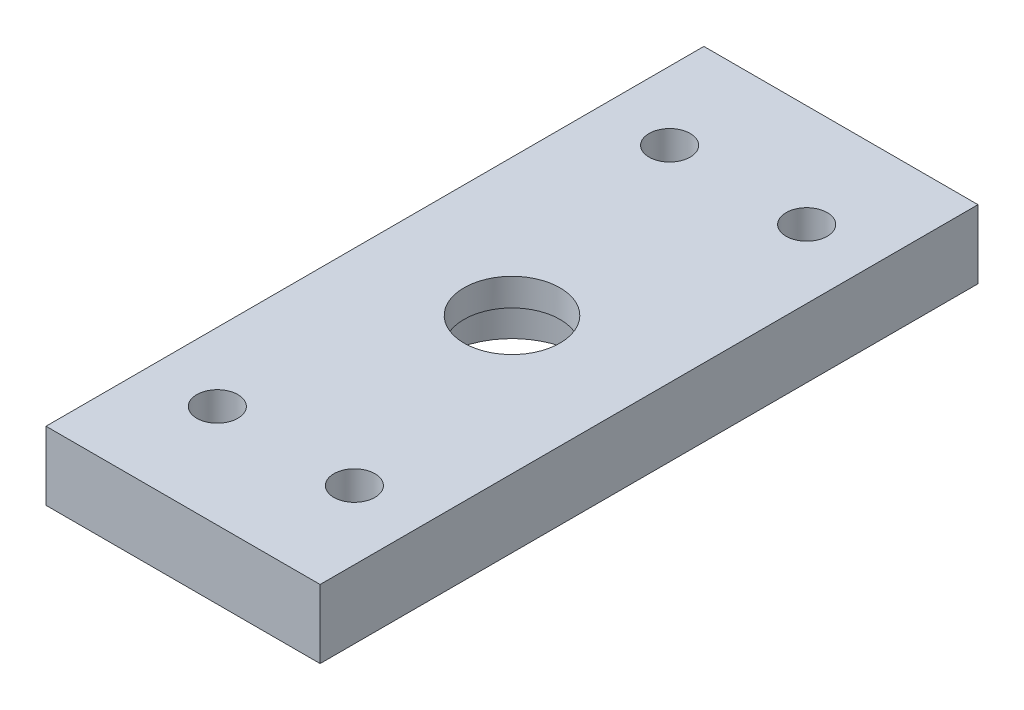
SolidWorks part; units mm, degrees
material "ABS"
ref_plane "Front Plane" through (0, 0, 0) normal (0, 0, 1) x (1, 0, 0)
ref_plane "Top Plane" through (0, 0, 0) normal (0, 1, 0) x (1, 0, 0)
ref_plane "Right Plane" through (0, 0, 0) normal (1, 0, 0) x (0, 0, -1)
sketch "Sketch1" plane through (0, 0, 0) normal (0, 1, 0) x (1, 0, 0)
  line L1 (-10, 24) -> (10, 24)
  line L2 (-10, 24) -> (-10, -24)
  line L3 (-10, -24) -> (10, -24)
  line L4 (10, 24) -> (10, -24)
  line L5 (-10, 24) -> (10, -24) construction
  line L6 (-10, -24) -> (10, 24) construction
  point P0 (0, 0)
  dimension "D1" = 20
  dimension "D2" = 48
extrude "Boss-Extrude1" add sketch "Sketch1" along normal blind 5
sketch "Sketch2" plane through (0, 5, 0) normal (0, 1, 0) x (1, 0, 0)
  circle A0 centre (0, 0) radius 3.5
  dimension "D1" = 7
extrude "Cut-Extrude1" cut sketch "Sketch2" against normal through all
sketch "Sketch3" plane through (0, 0, 0) normal (0, -1, 0) x (1, 0, 0)
  circle A0 centre (0, 0) radius 5
  dimension "D1" = 10
extrude "Cut-Extrude2" cut sketch "Sketch3" against normal blind 3
sketch "Sketch4" plane through (0, 0, 0) normal (0, -1, 0) x (1, 0, 0)
  circle A0 centre (5, -16.5) radius 1.5
  circle A1 centre (-5, -16.5) radius 1.5
  circle A2 centre (-5, 16.5) radius 1.5
  circle A3 centre (5, 16.5) radius 1.5
  dimension "D1" = 3
extrude "Cut-Extrude3" cut sketch "Sketch4" against normal through all
